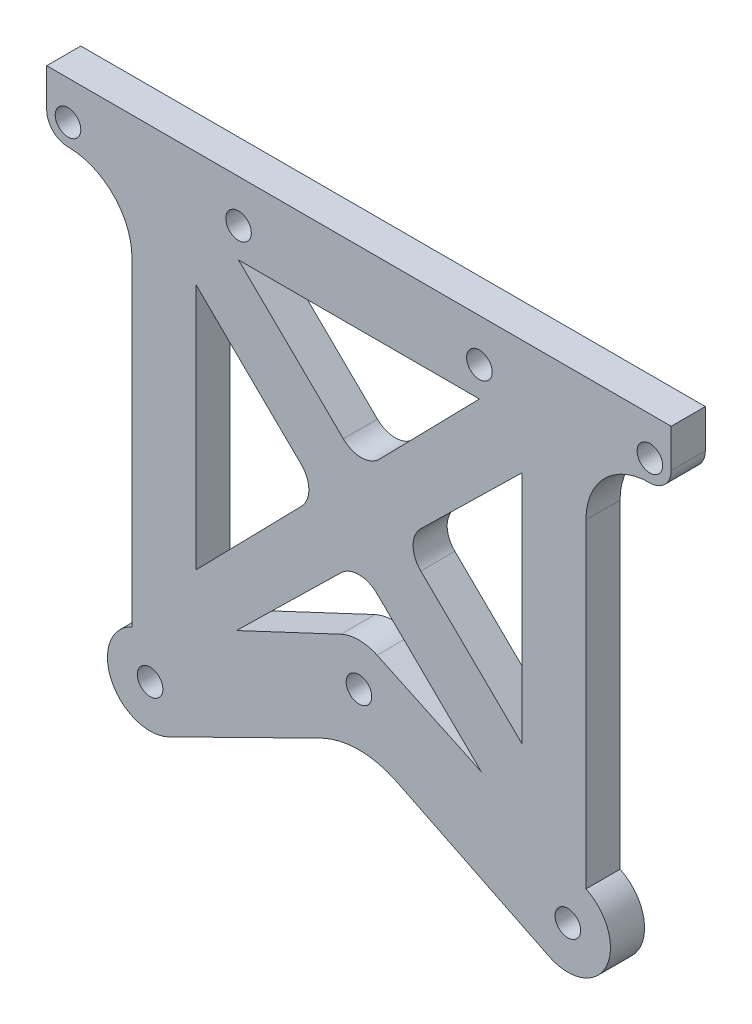
SolidWorks part; units mm, degrees
ref_plane "Front Plane" through (0, 0, 0) normal (0, 0, 1) x (1, 0, 0)
ref_plane "Top Plane" through (0, 0, 0) normal (0, 1, 0) x (1, 0, 0)
ref_plane "Right Plane" through (0, 0, 0) normal (1, 0, 0) x (0, 0, -1)
sketch "Sketch1" plane through (0, 0, 0) normal (0, 0, 1) x (1, 0, 0)
  line L0 (-22, 43.0262) -> (-34.1245, 43.0262)
  line L1 (-26.6245, -6.9738) -> (-22.3755, -16.0262) construction
  line L2 (-22.3755, -16.0262) -> (-4.4203, -7.1782)
  line L3 (0, 0) -> (-2.1245, 4.5262) construction
  line L4 (0, 0) -> (2.1245, 4.5262) construction
  line L5 (2.1245, 4.5262) -> (14.3745, -1.2238)
  line L6 (26.6245, -6.9738) -> (22.3755, -16.0262) construction
  line L7 (22.3755, -16.0262) -> (4.4203, -7.1782)
  line L8 (-26.6245, -6.9738) -> (-26.6245, 30.5262)
  line L9 (26.6245, -6.9738) -> (26.6245, 30.5262)
  line L10 (-19.1245, 2.5582) -> (-19.1245, 31.5466)
  line L11 (19.1245, 4.0207) -> (19.1245, 31.5466)
  line L12 (-22, 43.0262) -> (22, 43.0262)
  line L13 (-14.1245, 36.5466) -> (14.1245, 36.5466)
  line L14 (-19.1245, 31.5466) -> (-6.7784, 19.469)
  line L15 (-14.1245, 36.5466) -> (-1.8339, 24.5233)
  line L16 (14.1245, 36.5466) -> (2.4084, 24.57)
  line L17 (-14.3745, -1.2238) -> (-2.0979, 10.7858)
  line L18 (2.0979, 10.7858) -> (14.3745, -1.2238)
  line L19 (-6.7317, 15.2266) -> (-19.1245, 2.5582)
  line L20 (7.2478, 19.9282) -> (19.1245, 31.5466)
  line L21 (7.2478, 15.6392) -> (19.1245, 4.0207)
  line L22 (-14.3745, -1.2238) -> (-2.1245, 4.5262)
  line L23 (22, 43.0262) -> (34.1245, 43.0262)
  line L24 (0, 43.0262) -> (-22, 43.0262)
  line L25 (-36.6245, 40.5262) -> (-36.6245, 45.0262)
  line L26 (-36.6245, 45.0262) -> (36.6245, 45.0262)
  line L27 (36.6245, 45.0262) -> (36.6245, 40.5262)
  arc A3 (-26.6245, -6.9738) -> (-22.2051, -15.9422) centre (-24.5, -11.5) ccw
  arc A4 (2.1245, 4.5262) -> (-2.1245, 4.5262) centre (0, 0) ccw
  arc A5 (22.2051, -15.9422) -> (26.6245, -6.9738) centre (24.5, -11.5) ccw
  arc A6 (-4.4203, -7.1782) -> (4.4203, -7.1782) centre (0, -16.1482) cw
  arc A7 (-34.1245, 43.0262) -> (-34.1245, 38.0262) centre (-34.1245, 40.5262) ccw
  arc A8 (2.0979, 10.7858) -> (-2.0979, 10.7858) centre (0, 8.6413) ccw
  arc A9 (7.2478, 19.9282) -> (7.2478, 15.6392) centre (9.3457, 17.7837) ccw
  arc A10 (34.1245, 38.0262) -> (34.1245, 43.0262) centre (34.1245, 40.5262) ccw
  arc A11 (-6.7784, 19.469) -> (-6.7317, 15.2266) centre (-8.8762, 17.3245) cw
  arc A12 (2.4084, 24.57) -> (-1.8339, 24.5233) centre (0.2639, 26.6679) cw
  arc A13 (26.6245, 30.5262) -> (34.1245, 38.0262) centre (34.1245, 30.5262) cw
  arc A14 (-26.6245, 30.5262) -> (-34.1245, 38.0262) centre (-34.1245, 30.5262) ccw
  circle A15 centre (-34.1245, 40.5262) radius 1.5
  circle A16 centre (34.1245, 40.5262) radius 1.5
  circle A17 centre (-14.1245, 40.0262) radius 1.5
  circle A18 centre (14.1245, 40.0262) radius 1.5
  point P27 (-19.1245, 36.5466)
  point P30 (-26.6245, 43.0262)
  point P39 (5.0556, 17.7837)
  point P42 (-4.6339, 17.3711)
  circle B0 centre (-24.5, -11.5) radius 1.5
  circle B1 centre (0, 0) radius 1.5
  circle B2 centre (24.5, -11.5) radius 1.5
  dimension "D1" = 10
  dimension "D2" = 10
  dimension "D3" = 10
  dimension "D4" = 10
  dimension "D9" = 22
  dimension "D8" = 3
  dimension "D11" = 7.5
  dimension "D12" = 2.5
  dimension "D10" = 3
  dimension "D13" = 3
  dimension "D14" = 3
  dimension "D15" = 3
  dimension "D5" = 50
  dimension "D6" = 7.5
  dimension "D7" = 7.5
  dimension "D16" = 3
  dimension "D17" = 3
  dimension "D18" = 4.5
sketch_block_instance "Block1-1"
sketch_block "Block1"
extrude "Boss-Extrude1" add sketch "Sketch1" along normal blind 4
